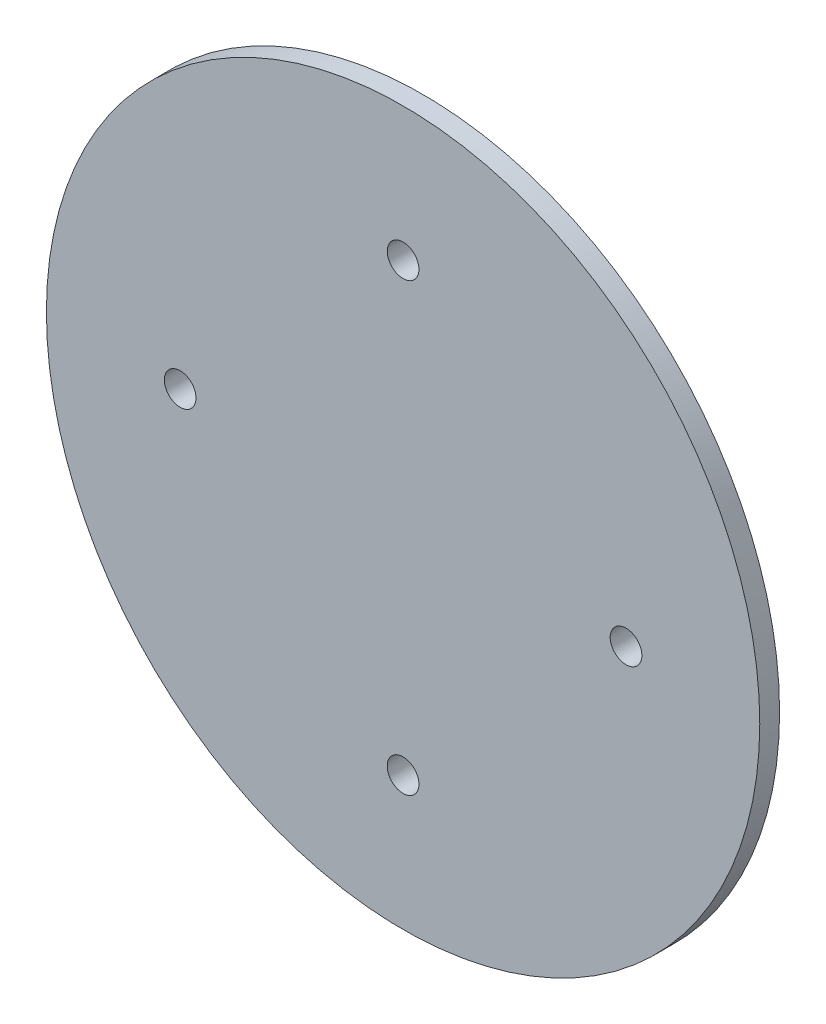
SolidWorks part; units mm, degrees
material "ABS"
ref_plane "正面" through (0, 0, 0) normal (0, 0, 1) x (1, 0, 0)
ref_plane "平面" through (0, 0, 0) normal (0, 1, 0) x (1, 0, 0)
ref_plane "右側面" through (0, 0, 0) normal (1, 0, 0) x (0, 0, -1)
sketch "ｽｹｯﾁ1" plane through (0, 0, 0) normal (0, 0, 1) x (1, 0, 0)
  circle A0 centre (0, 0) radius 27.5
  dimension "D1" = 55
extrude "ﾎﾞｽ - 押し出し1" add sketch "ｽｹｯﾁ1" along normal blind 4
sketch "ｽｹｯﾁ2" plane through (0, 0, 0) normal (0, 0, -1) x (-1, 0, 0)
  circle A0 centre (0, 0) radius 25.4
  dimension "D1" = 50.8
extrude "ﾎﾞｽ - 押し出し2" add sketch "ｽｹｯﾁ2" along normal blind 3.175
sketch "ｽｹｯﾁ3" plane through (0, 0, -3.175) normal (0, 0, -1) x (-1, 0, 0)
  circle A0 centre (0, 0) radius 22.5 construction
  circle A1 centre (0, 22.5) radius 1.6
  circle A2 centre (22.5, 0) radius 1.6
  circle A3 centre (0, -22.5) radius 1.6
  circle A4 centre (-22.5, 0) radius 1.6
  point P5 (-48.3635, -13.0673)
  point P6 (0, 0)
  point P14 (0, 0)
  dimension "D1" = 45
  dimension "D2" = 3.2
  dimension "D3" = 4
extrude "ｶｯﾄ - 押し出し1" cut sketch "ｽｹｯﾁ3" against normal through all
sketch "ｽｹｯﾁ4" plane through (0, 0, 4) normal (0, 0, 1) x (1, 0, 0)
  circle A0 centre (0, 0) radius 36
  circle A1 centre (0, 22.5) radius 1.6 construction
  circle A2 centre (-22.5, 0) radius 1.6 construction
  circle A3 centre (0, -22.5) radius 1.6 construction
  circle A4 centre (22.5, 0) radius 1.6 construction
  circle A5 centre (0, 22.5) radius 1.6
  circle A6 centre (-22.5, 0) radius 1.6
  circle A7 centre (0, -22.5) radius 1.6
  circle A8 centre (22.5, 0) radius 1.6
  dimension "D1" = 72
extrude "ﾎﾞｽ - 押し出し3" add sketch "ｽｹｯﾁ4" along normal blind 2
